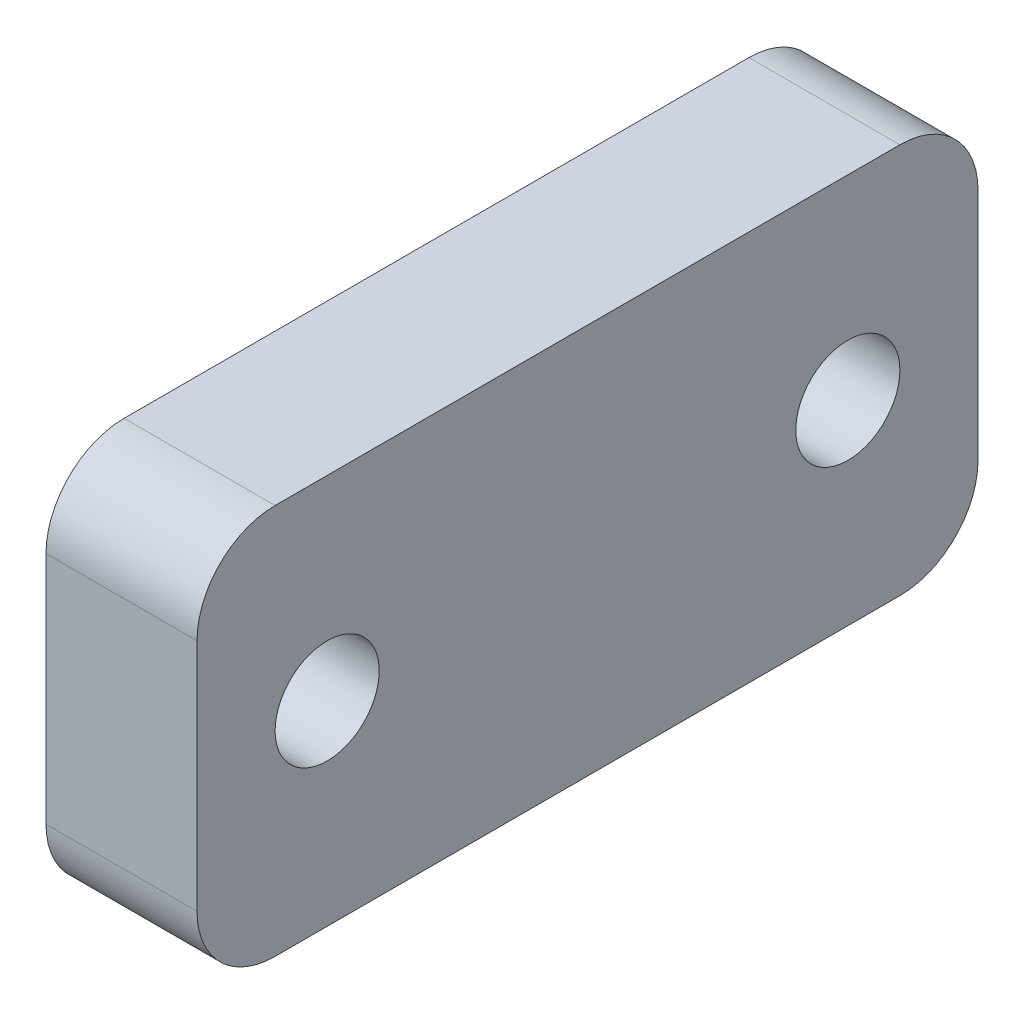
SolidWorks part; units mm, degrees
material "ナイロン"
ref_plane "正面" through (0, 0, 0) normal (0, 0, 1) x (1, 0, 0)
ref_plane "平面" through (0, 0, 0) normal (0, 1, 0) x (1, 0, 0)
ref_plane "右側面" through (0, 0, 0) normal (1, 0, 0) x (0, 0, -1)
sketch "ｽｹｯﾁ1" plane through (0, 0, 0) normal (1, 0, 0) x (0, 0, -1)
  line L0 (-15, 0) -> (15, 0) construction
  line L1 (-15, -7.5) -> (15, -7.5)
  line L2 (-15, -7.5) -> (-15, 7.5)
  line L3 (-15, 7.5) -> (15, 7.5)
  line L4 (15, -7.5) -> (15, 7.5)
  line L5 (-15, -7.5) -> (15, 7.5) construction
  line L6 (-15, 7.5) -> (15, -7.5) construction
  line L7 (0, 7.5) -> (0, -7.5) construction
  circle A0 centre (10, 0) radius 2
  circle A1 centre (-10, 0) radius 2
  point P0 (0, 0)
  dimension "D1" = 20
  dimension "D4" = 4
  dimension "D2" = 30
  dimension "D3" = 15
extrude "ﾎﾞｽ - 押し出し1" add sketch "ｽｹｯﾁ1" along normal blind 5.8
fillet "ﾌｨﾚｯﾄ1" radius 3 4 edges at (2.9, -7.5, 15) (2.9, -7.5, -15) (2.9, 7.5, -15) (2.9, 7.5, 15)
